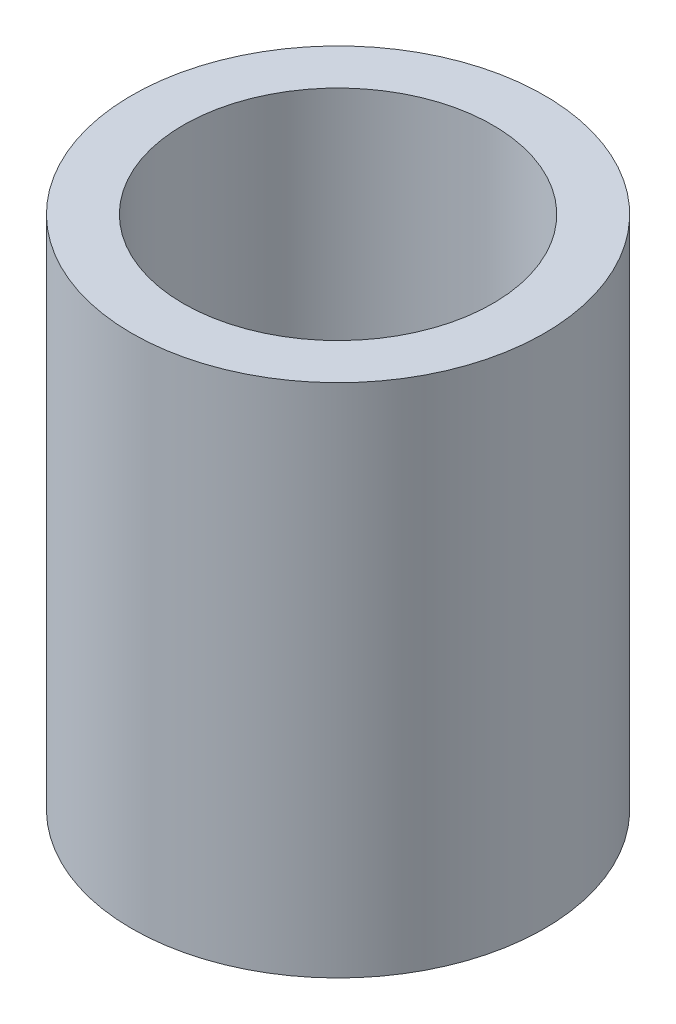
SolidWorks part; units mm, degrees
material "Alloy Steel"
ref_plane "Front Plane" through (0, 0, 0) normal (0, 0, 1) x (1, 0, 0)
ref_plane "Top Plane" through (0, 0, 0) normal (0, 1, 0) x (1, 0, 0)
ref_plane "Right Plane" through (0, 0, 0) normal (1, 0, 0) x (0, 0, -1)
sketch "Sketch1" plane through (0, 0, 0) normal (0, 1, 0) x (1, 0, 0)
  circle A0 centre (0, 0) radius 6
  circle A1 centre (0, 0) radius 8
  dimension "D1" = 12
  dimension "D2" = 2
extrude "Boss-Extrude1" add sketch "Sketch1" along normal blind 20
